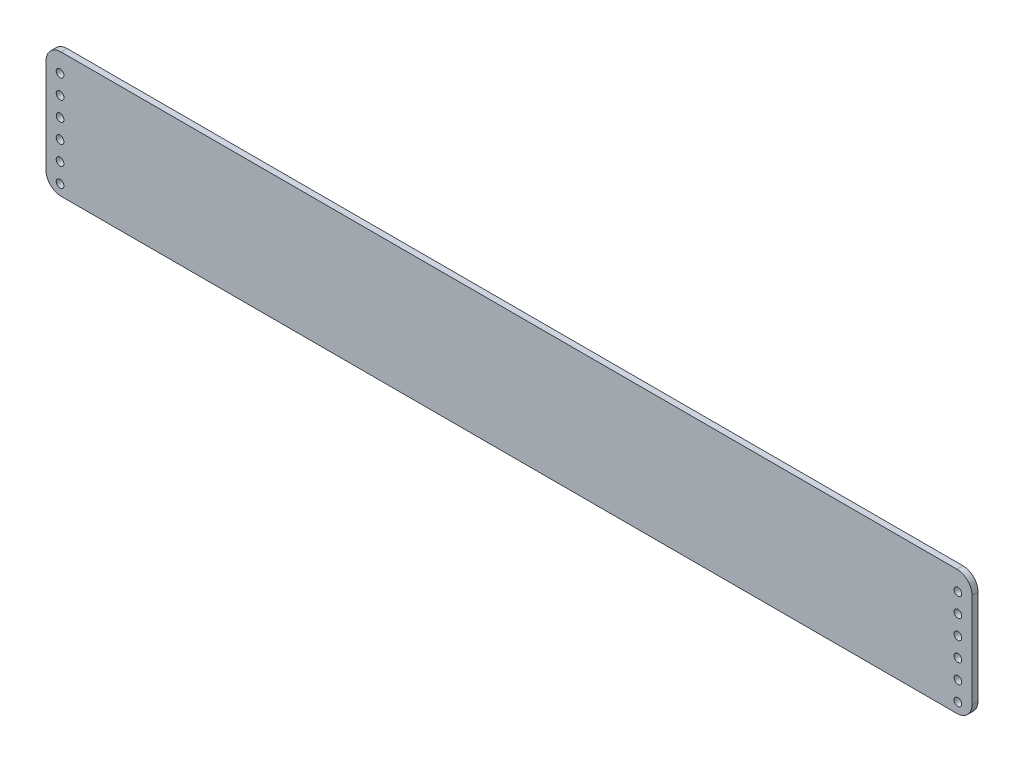
SolidWorks part; units mm, degrees
ref_plane "前视基准面" through (0, 0, 0) normal (0, 0, 1) x (1, 0, 0)
ref_plane "上视基准面" through (0, 0, 0) normal (0, 1, 0) x (1, 0, 0)
ref_plane "右视基准面" through (0, 0, 0) normal (1, 0, 0) x (0, 0, -1)
sketch "草图1" plane through (0, 0, 0) normal (0, 0, 1) x (1, 0, 0)
  line L0 (0, 41.5) -> (0, -41.5) construction
  line L1 (-307.5, 41.5) -> (307.5, 41.5)
  line L2 (-307.5, 41.5) -> (-307.5, -41.5)
  line L3 (-307.5, -41.5) -> (307.5, -41.5)
  line L4 (307.5, 41.5) -> (307.5, -41.5)
  line L5 (-307.5, 41.5) -> (307.5, -41.5) construction
  line L6 (-307.5, -41.5) -> (307.5, 41.5) construction
  circle A0 centre (-298.155, -34.6) radius 2.555
  circle A1 centre (-298.155, -21.9) radius 2.555
  circle A2 centre (-298.155, -9.2) radius 2.555
  circle A3 centre (-298.155, 3.5) radius 2.555
  circle A4 centre (-298.155, 16.2) radius 2.555
  circle A5 centre (298.155, 16.2) radius 2.555
  circle A6 centre (298.155, 3.5) radius 2.555
  circle A7 centre (298.155, -9.2) radius 2.555
  circle A8 centre (298.155, -21.9) radius 2.555
  circle A9 centre (298.155, -34.6) radius 2.555
  circle A10 centre (-298.155, 28.9) radius 2.555
  circle A11 centre (298.155, 28.9) radius 2.555
  point P0 (0, 0)
  dimension "D5" = 5.11
  dimension "D3" = 596.31
  dimension "D1" = 615
  dimension "D2" = 83
  dimension "D4" = 6.9
  dimension "D7" = 12.7
  dimension "D6" = 6
extrude "凸台-拉伸1" add sketch "草图1" along normal blind 4
fillet "圆角1" radius 10 4 edges at (-307.5, -41.5, 2) (-307.5, 41.5, 2) (307.5, -41.5, 2) (307.5, 41.5, 2)
